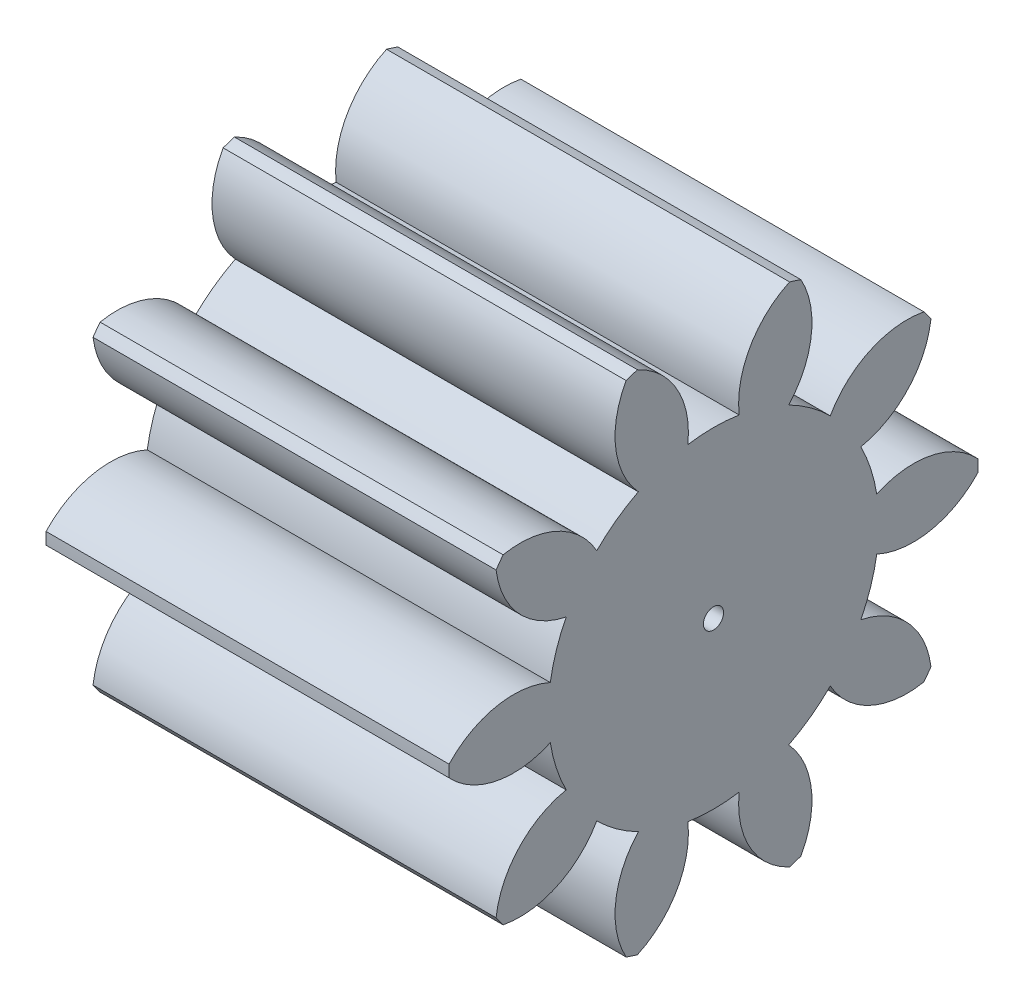
SolidWorks part; units mm, degrees
ref_plane "Plane1" through (0, 0, 0) normal (0, 0, 1) x (1, 0, 0)
ref_plane "Plane2" through (0, 0, 0) normal (0, 1, 0) x (1, 0, 0)
ref_plane "Plane3" through (0, 0, 0) normal (1, 0, 0) x (0, 0, -1)
sketch "HoldingSke" plane through (0, 0, 0) normal (0, 1, 0) x (1, 0, 0)
  line L0 (0, 0) -> (0.5627, -0.0992)
  line L1 (-15, 0) -> (100, 0) construction
  line L2 (0, 0) -> (-2.1039, 2.3779)
  line L3 (0, 0) -> (-11.863, 4.5341)
  line L4 (0, 0) -> (8.5048, 1.4996)
  line L5 (0, 0) -> (-46.8476, -17.4728)
  line L6 (0, 0) -> (-13.2634, -8.9489)
  line L7 (-2.1039, 2.3779) -> (8.6586, 51.2059)
  line L8 (-76.2, 54.61) -> (-76.1, 54.61)
  line L9 (-71.009, 38.7566) -> (-53.1078, 45.2721)
  line L10 (-76.2, 71.12) -> (104.1128, 71.12)
  line L11 (0, 0) -> (-16, 0)
  line L12 (-76.2, 101.6) -> (-76.147, 101.6)
  line L13 (24.9733, 27.94) -> (52.9518, 28.4284)
  line L14 (24.9733, 27.94) -> (24.9743, 27.94)
  line L15 (24.9733, 27.94) -> (100.4006, 29.5858)
  line L16 (-63.627, -1.75) -> (-12.827, -1.75)
  circle A0 centre (0, 0) radius 0.4
  circle A1 centre (0, 0) radius 6.5615
  circle A2 centre (0, 0) radius 37.5
  circle A3 centre (0, 0) radius 0.4
  dimension "Hub_dia" = 75
  dimension "Bore" = 0.8
  dimension "MBD" = 0.8
  dimension "Pitch" = 0.5714
  dimension "Overall_len" = 50
  dimension "OAL" = 50.0001
  dimension "T_dim" = 0.1
  dimension "Ap" = 20
  dimension "H" = 19.05
  dimension "Pitch_radius" = 180.3128
  dimension "Backlash" = 0.053
  dimension "Addendum_fac" = 1
  dimension "Dedendum_fac" = 1.25
  dimension "Clearance_fac" = 0.25
  dimension "Dedendum_add" = 0.001
  dimension "Module" = 1.75
sketch "BasProSke" plane through (0, 0, 0) normal (0, 1, 0) x (1, 0, 0)
  line L0 (-10, 0) -> (60, 0) construction
  line L1 (0, 0) -> (0, 10.5)
  line L2 (0, 0) -> (16, 0)
  line L3 (16, 0) -> (16, 10.5)
  line L4 (16, 10.5) -> (0, 10.5)
revolve "Base-Revolve" add sketch "BasProSke" angle 360 about L0
sketch "TooCutSke" plane through (0, 0, 0) normal (1, 0, 0) x (0, 0, -1)
  line L1 (0, 0) -> (0, 107) construction
  line L2 (0, 0) -> (-1.4614, 8.6271) construction
  line L3 (0, 0) -> (-5.35, 16.4656) construction
  line L4 (-1.4614, 8.6271) -> (-2.675, 8.2328) construction
  arc A0 (1.0196, 6.4818) -> (-1.0196, 6.4818) centre (0, 0) ccw
  arc A1 (3.0536, 10.0727) -> (-3.0536, 10.0727) centre (0, 0) ccw
  circle A2 centre (0, 0) radius 8.75 construction
  circle A3 centre (0, 0) radius 8.2223 construction
  arc A4 (-1.0196, 6.4818) -> (-3.0536, 10.0727) centre (-4.4964, 6.8839) ccw
  arc A5 (3.0536, 10.0727) -> (1.0196, 6.4818) centre (4.4964, 6.8839) ccw
  dimension "Half_CT" = 1.2761
extrude "ToothCut" cut sketch "TooCutSke" along normal through all
fillet "Breaks" [suppressed] radius 0.035
fillet "RootFillets" [suppressed] radius 0.4385
pattern_circular "TeethCuts" count 10 every 36 about axis through (-10, 0, 0) along (1, 0, 0) of "ToothCut", "RootFillets", "Breaks"
sketch "HubNeaOneSke" plane through (0, 0, 0) normal (-1, 0, 0) x (0, 0, 1)
  circle A0 centre (0, 0) radius 6.5615
extrude "HubNearOne" [suppressed] add sketch "HubNeaOneSke" along normal blind 34.0001
sketch "HubNeaBotSke" plane through (0, 0, 0) normal (-1, 0, 0) x (0, 0, 1)
  circle A0 centre (0, 0) radius 6.5615
extrude "HubNearBoth" [suppressed] add sketch "HubNeaBotSke" along normal blind 17
ref_plane "FarPln" through (16, 0, 0) normal (1, 0, 0) x (0, 0, -1)
sketch "HubFarSke" plane through (16, 0, 0) normal (1, 0, 0) x (0, 0, -1)
  circle A0 centre (0, 0) radius 6.5615
extrude "HubFar" [suppressed] add sketch "HubFarSke" along normal blind 17
sketch "BorSke" plane through (0, 0, 0) normal (1, 0, 0) x (0, 0, -1)
  circle A0 centre (0, 0) radius 0.4
  dimension "Diameter" = 0.8
extrude "Bore" cut sketch "BorSke" along normal mid plane 100.0001
sketch "KeySke" plane through (0, 0, 0) normal (1, 0, 0) x (0, 0, -1)
  line L0 (-0.05, 0) -> (-0.05, 0.5)
  line L1 (-0.05, 0.5) -> (0.05, 0.5)
  line L2 (0.05, 0.5) -> (0.05, 0)
  line L3 (0, 0) -> (0, 34) construction
  line L4 (-0.05, 0) -> (0.05, 0)
  dimension "Offset" = 0.5
  dimension "Width" = 0.1
extrude "Keyway" [suppressed] cut sketch "KeySke" along normal mid plane 100.0001
pattern_circular "Keyway2" [suppressed] count 2 every 90 about axis through (-10, 0, 0) along (1, 0, 0)
equation "' \"Module@HoldingSke\" = 6.35"
equation "' \"Num_teeth@HoldingSke\" = 12"
equation "' \"Ap@HoldingSke\" =  20"
equation "' \"Ap@HoldingSke\" = 20"
equation "' \"Width@HoldingSke\" = 0.5 * 25.4"
equation "' \"Hub_dia@HoldingSke\"= 1 * 25.4"
equation "' \"Hub_dia@HoldingSke\" = 1 * 25.4"
equation "' \"Overall_len@HoldingSke\" = 1.0 * 25.4"
equation "' \"Bore@HoldingSke\" = 0.75 * 25.4"
equation "' \"T_dim@HoldingSke\" = 0.1 * 25.4"
equation "' \"Width@KeySke\" = 0.25 * 25.4"
equation "' \"Show_teeth@HoldingSke\" = 13"
equation "' \"Backlash@HoldingSke\" = 0.009 * 25.4"
equation "' \"Addendum_fac@HoldingSke\" = 1.0"
equation "' \"Dedendum_fac@HoldingSke\" = 1.25"
equation "' \"Dedendum_add@HoldingSke\" = 0.00005 * 25.4"
equation "' \"Clearance_fac@HoldingSke\" = 0.25"
equation "\"Pitch@HoldingSke\" = 1 / \"Module@HoldingSke\""
equation "\"Overcut_dia@TooCutSke\" = (\"Num_teeth@HoldingSke\" + 2 * \"Addendum_fac@HoldingSke\") / \"Pitch@HoldingSke\" + 0.002 * 25.4"
equation "\"Pitch_dia@TooCutSke\" = \"Num_teeth@HoldingSke\" / \"Pitch@HoldingSke\""
equation "\"Base_dia@TooCutSke\" = \"Num_teeth@HoldingSke\" / \"Pitch@HoldingSke\" * cos((\"Ap@HoldingSke\"  * 3.14159265 / 180))"
equation "\"Root_dia@TooCutSke\" = (\"Num_teeth@HoldingSke\" + 2) / \"Pitch@HoldingSke\" - 2 * (\"Addendum_fac@HoldingSke\" + \"Dedendum_fac@HoldingSke\") / \"Pitch@HoldingSke\" - \"Dedendum_add@HoldingSke\" * 2"
equation "\"Half_ang@TooCutSke\" = 180 / \"Num_teeth@HoldingSke\""
equation "\"Half_CT@TooCutSke\" = \"Num_teeth@HoldingSke\" / \"Pitch@HoldingSke\" * sin((3.14159265 / 2 / \"Num_teeth@HoldingSke\")) / 2 - 7 * \"Backlash@HoldingSke\" / 4"
equation "\"Flank_rad@TooCutSke\" = \"Num_teeth@HoldingSke\" / \"Pitch@HoldingSke\" / 5"
equation "\"Radius@RootFillets\" = \"Clearance_fac@HoldingSke\" / \"Pitch@HoldingSke\" + \"Dedendum_add@HoldingSke\""
equation "\"Break_rad@Breaks\" = 0.02 / \"Pitch@HoldingSke\""
equation "\"Thickness@HoldingSke\" = \"Width@HoldingSke\""
equation "\"OAL@HoldingSke\" = \"Thickness@HoldingSke\""
equation "\"MHD@HoldingSke\" = (\"Num_teeth@HoldingSke\" + 2) / \"Pitch@HoldingSke\" - 2 * (\"Addendum_fac@HoldingSke\" + \"Dedendum_fac@HoldingSke\")  / \"Pitch@HoldingSke\" - \"Dedendum_add@HoldingSke\" * 2"
equation "\"MBD@HoldingSke\" = (\"Num_teeth@HoldingSke\" + 2) / \"Pitch@HoldingSke\" - 2 * (\"Addendum_fac@HoldingSke\" + \"Dedendum_fac@HoldingSke\")  / \"Pitch@HoldingSke\" - \"Dedendum_add@HoldingSke\" * 2 - 0.002 * 25.4"
equation "\"MHD@HoldingSke\" = ((sgn( \"MHD@HoldingSke\" - \"Hub_dia@HoldingSke\" )-1)*( \"MHD@HoldingSke\" - \"Hub_dia@HoldingSke\" ))/-2+ \"Hub_dia@HoldingSke\""
equation "\"MBD@HoldingSke\" = ((sgn( \"MBD@HoldingSke\" - \"Bore@HoldingSke\" )-1)*( \"MBD@HoldingSke\" - \"Bore@HoldingSke\" ))/-2+ \"Bore@HoldingSke\""
equation "\"OAL@HoldingSke\" = ((sgn( \"OAL@HoldingSke\" - \"Overall_len@HoldingSke\" )+1)*( \"OAL@HoldingSke\" - \"Overall_len@HoldingSke\" ))/2 + \"Overall_len@HoldingSke\" + 0.000002 * 25.4"
equation "\"Num_teeth@TeethCuts\" = int( \"Show_teeth@HoldingSke\" ) + 1"
equation "\"Num_teeth@TeethCuts\" = ((sgn( \"Num_teeth@TeethCuts\" - \"Num_teeth@HoldingSke\" )-1)*( \"Num_teeth@TeethCuts\" - \"Num_teeth@HoldingSke\" ))/-2+ \"Num_teeth@HoldingSke\""
equation "\"Num_teeth@TeethCuts\" = ((sgn( \"Num_teeth@TeethCuts\" - 2.0)+1)*( \"Num_teeth@TeethCuts\" - 2.0))/2 +2.0"
equation "\"Angle@TeethCuts\" = 360.0 / \"Num_teeth@HoldingSke\""
equation "\"Diameter@BasProSke\" = (\"Num_teeth@HoldingSke\" + 2 * \"Addendum_fac@HoldingSke\") / \"Pitch@HoldingSke\""
equation "\"Thickness@BasProSke\"  = \"Thickness@HoldingSke\""
equation "' \"Fillet_rad@BasProSke\" =  \"Thickness@HoldingSke\" * 0.05"
equation "' \"Fillet_rad@BasProSke\" = \"Thickness@HoldingSke\" * 0.05"
equation "\"MHD@HoldingSke\" = ((sgn( \"MHD@HoldingSke\" - \"Root_dia@TooCutSke\" )-1)*( \"MHD@HoldingSke\" - \"Root_dia@TooCutSke\" ))/-2+ \"Root_dia@TooCutSke\""
equation "\"Diameter@HubNeaOneSke\" = \"MHD@HoldingSke\""
equation "\"Length@HubNearOne\" = \"OAL@HoldingSke\" - \"Thickness@BasProSke\""
equation "\"Diameter@HubNeaBotSke\" = \"MHD@HoldingSke\""
equation "\"Length@HubNearBoth\" = ( \"OAL@HoldingSke\" - \"Thickness@BasProSke\" ) / 2.0"
equation "\"Thickness@FarPln\" = \"Thickness@BasProSke\""
equation "\"Diameter@HubFarSke\" = \"MHD@HoldingSke\""
equation "\"Length@HubFar\" = ( \"OAL@HoldingSke\" - \"Thickness@BasProSke\" ) / 2.0"
equation "\"Diameter@BorSke\" = \"MBD@HoldingSke\""
equation "\"D1@Bore\" = \"OAL@HoldingSke\" * 2.0"
equation "\"D1@Keyway\" = \"OAL@HoldingSke\" * 2.0"
equation "\"Offset@KeySke\" = \"T_dim@HoldingSke\" + \"MBD@HoldingSke\" / 2.0"
